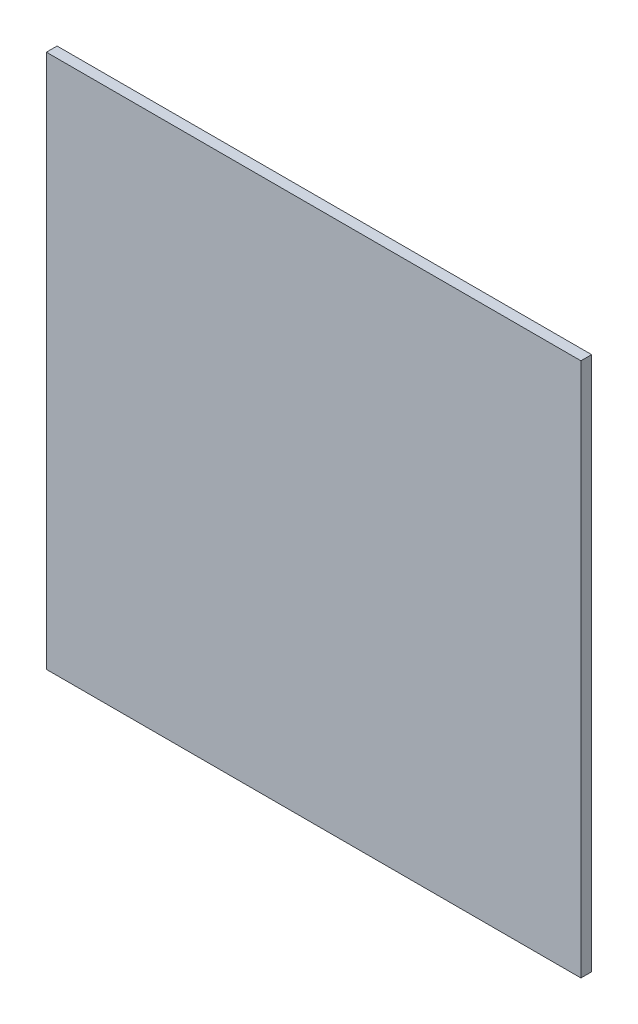
SolidWorks part; units mm, degrees
ref_plane "Alzado" through (0, 0, 0) normal (0, 0, 1) x (1, 0, 0)
ref_plane "Planta" through (0, 0, 0) normal (0, 1, 0) x (1, 0, 0)
ref_plane "Vista lateral" through (0, 0, 0) normal (1, 0, 0) x (0, 0, -1)
sketch "Croquis1" plane through (0, 0, 0) normal (0, 0, 1) x (1, 0, 0)
  line L1 (-75, -75) -> (75, -75)
  line L2 (-75, -75) -> (-75, 75)
  line L3 (-75, 75) -> (75, 75)
  line L4 (75, -75) -> (75, 75)
  line L5 (-75, -75) -> (75, 75) construction
  line L6 (-75, 75) -> (75, -75) construction
  point P0 (0, 0)
  dimension "D1" = 150
  dimension "D2" = 150
extrude "Saliente-Extruir1" add sketch "Croquis1" along normal blind 3
